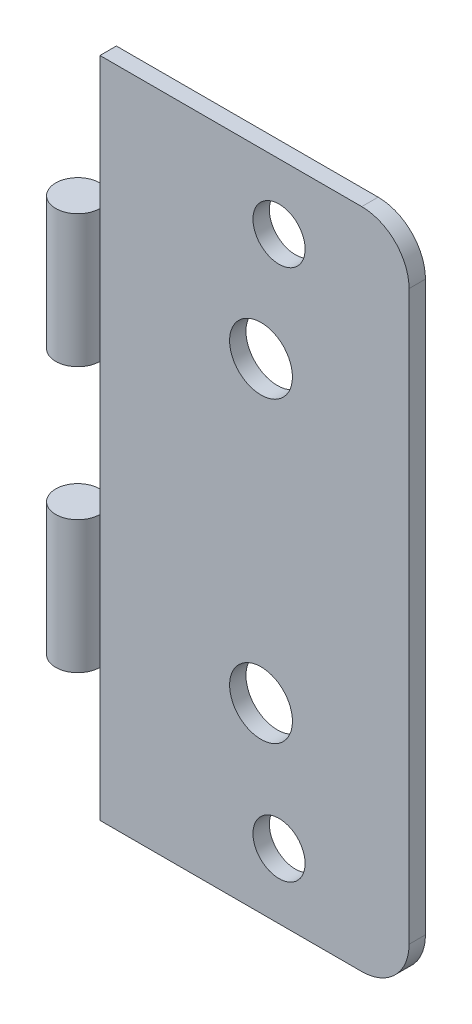
SolidWorks part; units mm, degrees
ref_plane "Front Plane" through (0, 0, 0) normal (0, 0, 1) x (1, 0, 0)
ref_plane "Top Plane" through (0, 0, 0) normal (0, 1, 0) x (1, 0, 0)
ref_plane "Right Plane" through (0, 0, 0) normal (1, 0, 0) x (0, 0, -1)
sketch "Sketch1" plane through (0, 0, 0) normal (0, 1, 0) x (1, 0, 0)
  line L1 (0, 0) -> (44.45, 0)
  line L2 (0, 0) -> (0, 2.2)
  line L3 (0, 2.2) -> (44.45, 2.2)
  line L4 (44.45, 0) -> (44.45, 2.2)
  circle A1 centre (0, 0) radius 2.97
  dimension "D1" = 5.94
  dimension "D2" = 2.2
  dimension "D3" = 44.45
extrude "Boss-Extrude1" add sketch "Sketch1" along normal mid plane 88.9 contours A1 | L1 L4 L3 L2
sketch "Sketch2" plane through (0, 0, 0) normal (0, 0, 1) x (1, 0, 0)
  line L0 (-2.97, -8.89) -> (-2.97, -26.67) construction
  line L5 (-2.97, 44.45) -> (-2.97, -44.45) construction
  line L6 (2.97, 44.45) -> (2.97, -44.45) construction
  line L11 (-2.97, 26.67) -> (-2.97, 8.89) construction
  line L12 (-2.97, 44.45) -> (2.97, 44.45)
  line L13 (-2.97, 44.45) -> (-2.97, 26.67)
  line L14 (-2.97, 26.67) -> (2.97, 26.67)
  line L15 (2.97, 44.45) -> (2.97, 26.67)
  line L17 (-2.97, 8.89) -> (2.97, 8.89)
  line L18 (-2.97, 8.89) -> (-2.97, -8.89)
  line L19 (-2.97, -8.89) -> (2.97, -8.89)
  line L20 (2.97, 8.89) -> (2.97, -8.89)
  line L21 (-2.97, -26.67) -> (2.97, -26.67)
  line L22 (-2.97, -26.67) -> (-2.97, -44.45)
  line L23 (-2.97, -44.45) -> (2.97, -44.45)
  line L24 (2.97, -26.67) -> (2.97, -44.45)
extrude "Cut-Extrude1" cut sketch "Sketch2" against normal through all and the other way through all
fillet "Fillet1" radius 6.35 2 edges at (44.45, -44.45, -1.1) (44.45, 44.45, -1.1)
sketch "Sketch4" plane through (0, 0, 0) normal (0, 0, 1) x (1, 0, 0)
  line L0 (2.97, -44.45) -> (38.1, -44.45) construction
  line L1 (44.45, 38.1) -> (44.45, -38.1) construction
  line L2 (2.97, 44.45) -> (38.1, 44.45) construction
  circle A0 centre (27, 35.7) radius 3.5
  circle A1 centre (27, -35.7) radius 3.5
  dimension "D1" = 7
  dimension "D2" = 8.75
  dimension "D3" = 17.45
  dimension "D4" = 8.75
extrude "Cut-Extrude2" cut sketch "Sketch4" against normal through all
hole_wizard "5/16 Clearance Hole1" positions "Sketch7" profile "Sketch6" hole size "5/16" standard "ANSI Inch" end condition through all
sketch "Sketch7" plane through (0, 0, 0) normal (0, 0, 1) x (1, 0, 0)
  line L0 (24.5812, 20.0103) -> (24.5813, 0) construction
  line L1 (24.5813, 0) -> (24.5812, -20.0103) construction
  circle A0 centre (27, 35.7) radius 3.5 construction
  point P0 (24.5812, 20.0103)
  point P2 (24.5812, -20.0103)
  dimension "D1" = 24.5813
  dimension "D2" = 15.875
sketch "Sketch6" plane through (24.5812, 20.0103, 0) normal (1, 0, 0) x (0, -1, 0)
  line L0 (0, 0) -> (0, 2.97)
  line L1 (0, 2.97) -> (4.2164, 2.97)
  line L2 (4.2164, 2.97) -> (4.2164, 0)
  line L5 (4.2164, 0) -> (0, 0)
  line L11 (0, -6.35) -> (0, 107.95) construction
  dimension "Thru Hole Dia." = 8.4328
  dimension "Thru Hole Depth" = 2.97
